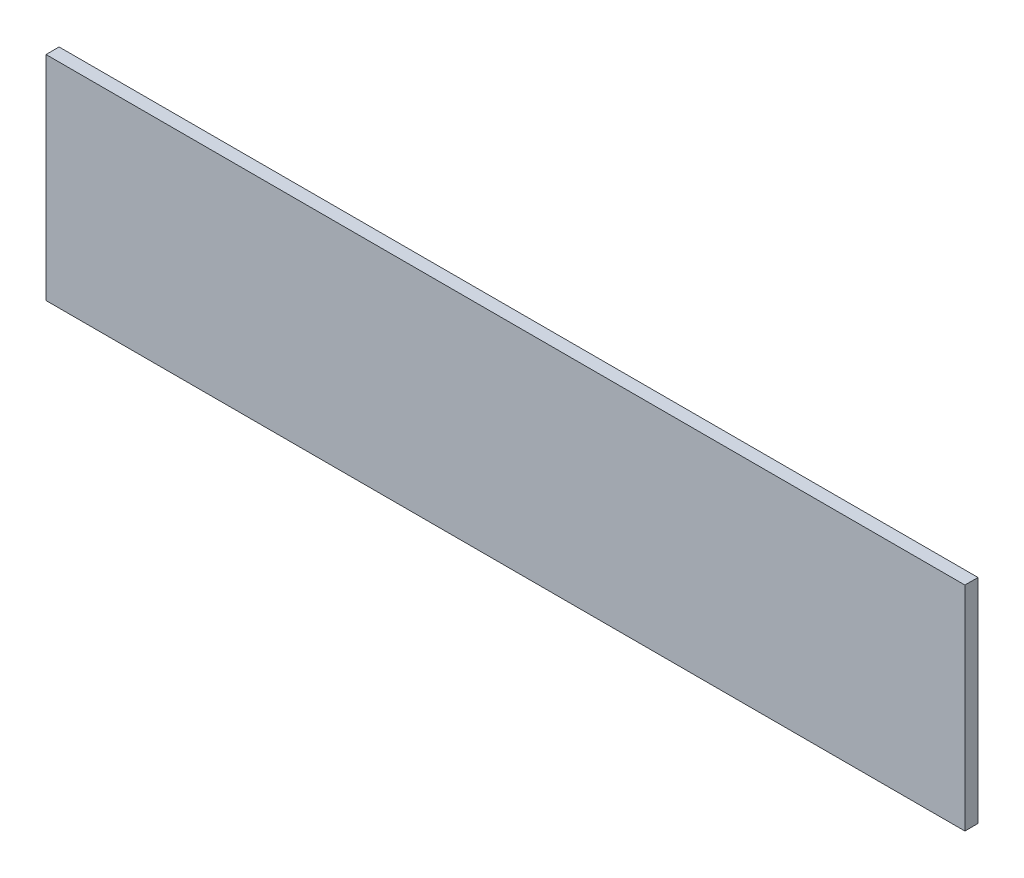
SolidWorks part; units mm, degrees
material "6061 Alloy"
ref_plane "Front Plane" through (0, 0, 0) normal (0, 0, 1) x (1, 0, 0)
ref_plane "Top Plane" through (0, 0, 0) normal (0, 1, 0) x (1, 0, 0)
ref_plane "Right Plane" through (0, 0, 0) normal (1, 0, 0) x (0, 0, -1)
sketch "Sketch1" plane through (0, 0, 0) normal (0, 0, 1) x (1, 0, 0)
  line L1 (-227.6475, 72.4694) -> (-8.5725, 72.4694)
  line L2 (-227.6475, 72.4694) -> (-227.6475, 21.6694)
  line L3 (-227.6475, 21.6694) -> (-8.5725, 21.6694)
  line L4 (-8.5725, 72.4694) -> (-8.5725, 21.6694)
  dimension "D1" = 50.8
  dimension "D2" = 219.075
extrude "Boss-Extrude1" add sketch "Sketch1" along normal blind 3.1242
